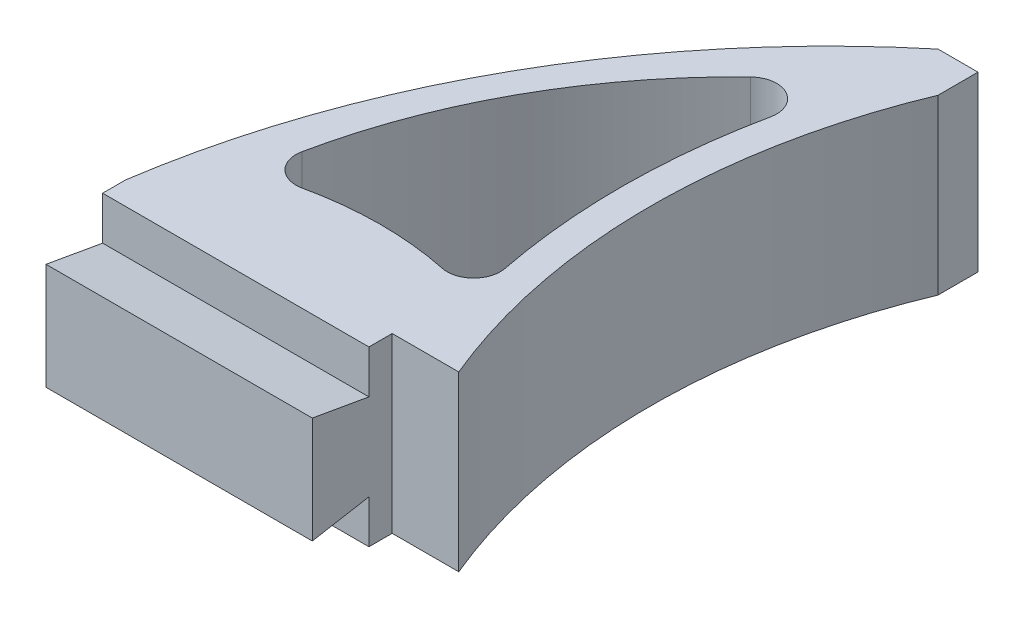
SolidWorks part; units mm, degrees
ref_plane "前视基准面" through (0, 0, 0) normal (0, 0, 1) x (1, 0, 0)
ref_plane "上视基准面" through (0, 0, 0) normal (0, 1, 0) x (1, 0, 0)
ref_plane "右视基准面" through (0, 0, 0) normal (1, 0, 0) x (0, 0, -1)
other "Configuration Table"
sketch "草图1" plane through (0, 0, 0) normal (0, 1, 0) x (1, 0, 0)
  line L6 (0, 0) -> (0, 6)
  line L7 (22, 45) -> (25, 45)
  line L8 (25, 45) -> (25, 42)
  line L9 (25, 6) -> (20, 6)
  line L10 (20, 6) -> (20, 0)
  line L11 (20, 0) -> (0, 0)
  arc A2 (0, 6) -> (22, 45) centre (62.0554, -3.3005) cw
  arc A3 (25, 42) -> (25, 6) centre (68.4166, 24) ccw
  point P2 (23.5, 45)
  point P9 (0, 0)
  point P13 (-73.7329, 65.9384)
  dimension "D6" = 25
  dimension "D7" = 39
  dimension "D5" = 47
  dimension "D1" = 6
  dimension "D2" = 20
  dimension "D3" = 5
  dimension "D4" = 3
extrude "凸台-拉伸1" add sketch "草图1" along normal mid plane 13
sketch "草图3" plane through (0, 0, 0) normal (-1, 0, 0) x (0, 0, 1)
  line L0 (0, 0) -> (-4.7083, 0) construction
  line L1 (0, 6.5) -> (0, -6.5) construction
  line L2 (0, 4) -> (0, 6.5)
  line L3 (-6, 6.5) -> (0, 6.5) construction
  line L4 (-4.2535, 3.25) -> (-4.2535, 6.5)
  line L5 (-4.2535, 6.5) -> (0, 6.5)
  line L6 (0, 4) -> (-4.2535, 3.25)
  line L7 (0, -4) -> (-4.2535, -3.25)
  line L8 (-4.2535, -6.5) -> (0, -6.5)
  line L9 (-4.2535, -3.25) -> (-4.2535, -6.5)
  line L10 (0, -6.5) -> (0, -4)
  dimension "D1" = 6.5
  dimension "D2" = 8
  dimension "D3" = 80
extrude "切除-拉伸1" cut sketch "草图3" against normal through all
sketch "草图4" plane through (0, 6.5, 0) normal (0, 1, 0) x (1, 0, 0)
  line L0 (25, 6) -> (0, 6) construction
  line L1 (12.5, 6) -> (12.5, 22.9778) construction
  line L2 (20, 4.2535) -> (0, 4.2535) construction
  arc A0 (7.1697, 12.0791) -> (17.6352, 12.1208) centre (12.5, -12.3461) cw
  arc A1 (4.7851, 14.44) -> (16.7763, 36.1516) centre (45.9069, 5.8959) cw
  arc A2 (20.1214, 34.3029) -> (20.0085, 14.4638) centre (69.0703, 24.1045) ccw
  arc A4 (16.7763, 36.1516) -> (20.1214, 34.3029) centre (18.1635, 34.7108) cw
  arc A5 (17.6352, 12.1208) -> (20.0085, 14.4638) centre (18.0461, 14.0782) ccw
  arc A6 (7.1697, 12.0791) -> (4.7851, 14.44) centre (6.7433, 14.0331) cw
  point P12 (0, 0)
  point P13 (19.5776, 30.5631)
  point P16 (20.75, 38.3662)
  point P19 (35.8482, 24.8546)
  point P20 (21.75, 40.2535)
  point P23 (44.0061, 16.7817)
  point P24 (20.75, 11.2535)
  point P27 (4.25, 11.2535)
  dimension "D3" = 25
  dimension "D4" = 42
  dimension "D5" = 50
  dimension "D8" = 2
  dimension "D1" = 16.5
  dimension "D2" = 7
  dimension "D6" = 17.5
  dimension "D7" = 29
extrude "切除-拉伸2" cut sketch "草图4" against normal through all
